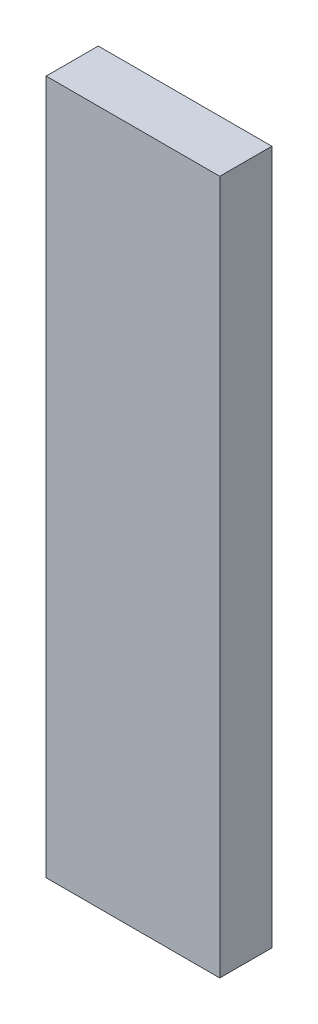
SolidWorks part; units mm, degrees
ref_plane "Front Plane" through (0, 0, 0) normal (0, 0, 1) x (1, 0, 0)
ref_plane "Top Plane" through (0, 0, 0) normal (0, 1, 0) x (1, 0, 0)
ref_plane "Right Plane" through (0, 0, 0) normal (1, 0, 0) x (0, 0, -1)
sketch "Sketch1" plane through (0, 0, 0) normal (0, 0, 1) x (1, 0, 0)
  line L1 (-5, -20) -> (5, -20)
  line L2 (-5, -20) -> (-5, 20)
  line L3 (-5, 20) -> (5, 20)
  line L4 (5, -20) -> (5, 20)
  line L5 (-5, -20) -> (5, 20) construction
  line L6 (-5, 20) -> (5, -20) construction
  point P0 (0, 0)
  dimension "D1" = 10
  dimension "D2" = 40
extrude "Boss-Extrude1" add sketch "Sketch1" along normal blind 3
